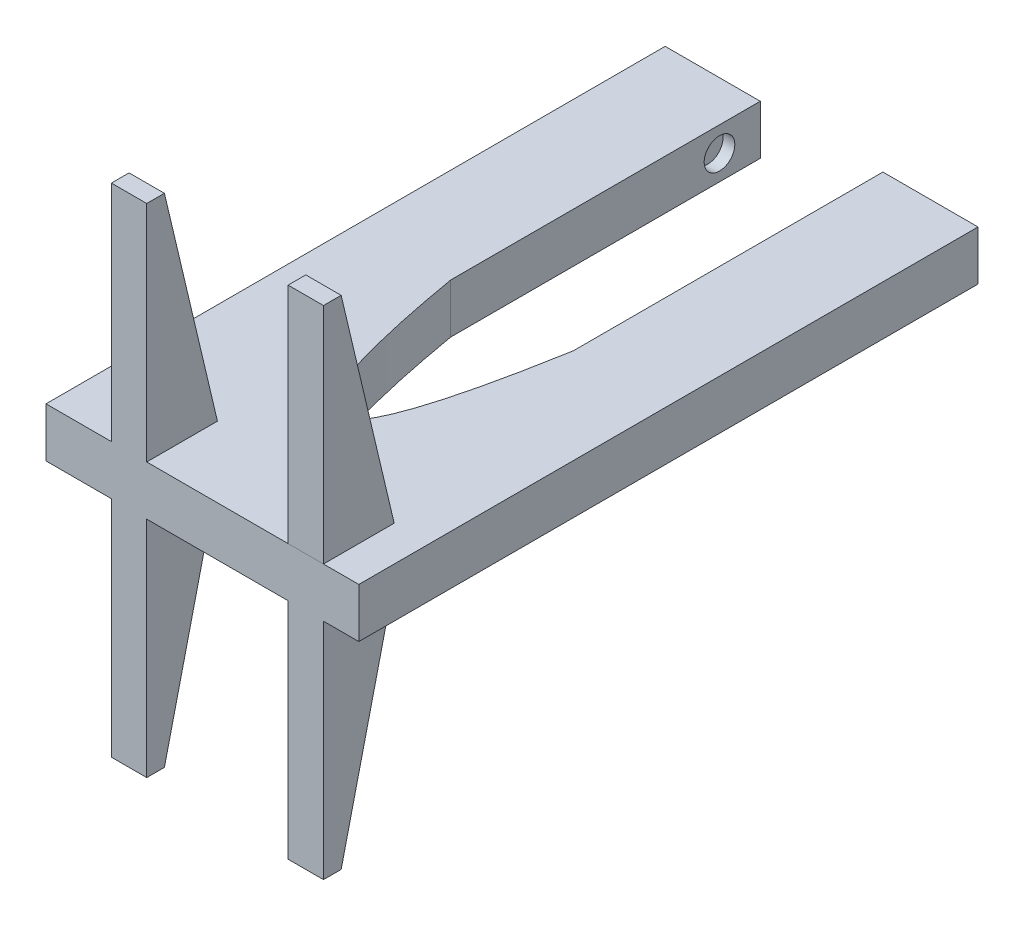
SolidWorks part; units mm, degrees
material "Ductile Iron"
ref_plane "Front Plane" through (0, 0, 0) normal (0, 0, 1) x (1, 0, 0)
ref_plane "Top Plane" through (0, 0, 0) normal (0, 1, 0) x (1, 0, 0)
ref_plane "Right Plane" through (0, 0, 0) normal (1, 0, 0) x (0, 0, -1)
sketch "Sketch1" plane through (0, 0, 0) normal (0, 1, 0) x (1, 0, 0)
  line L1 (300, 0) -> (300, -5255)
  line L2 (300, -5255) -> (-2355, -5255)
  line L3 (-2355, -5255) -> (-2355, -4455)
  line L6 (-2355, 0) -> (-2355, -4455)
  line L8 (-2355, 0) -> (-1548, 0)
  line L9 (300, 0) -> (-507, 0)
  line L10 (-1548, 0) -> (-1548, -2627.5)
  line L11 (-507, 0) -> (-507, -2627.5)
  spline S0 degree 2 poles (-1548, -2627.5) (-1027.5, -5612.8869) (-507, -2627.5) knots 0 0 0 1 1 1
  point P12 (0, 0)
  point P13 (0, 0)
  dimension "D5" = 807
  dimension "D1" = 5255
  dimension "D2" = 2655
  dimension "D3" = 800
  dimension "D6" = 807
extrude "Boss-Extrude1" add sketch "Sketch1" along normal blind 420
ref_plane "Plane1" through (0, 0, 0) normal (1, 0, 0) x (0, 0, -1)
ref_plane "Plane2" through (-1800, 0, 0) normal (1, 0, 0) x (0, 0, -1)
sketch "Sketch2" plane through (-1800, 0, 0) normal (1, 0, 0) x (0, 0, -1)
  line L0 (-5255, 420) -> (-5255, 2320)
  line L1 (-5105, 2320) -> (-4655, 420)
  line L2 (-5255, 420) -> (0, 420) construction
  line L3 (-4655, 420) -> (-5255, 420)
  line L4 (-5255, 2320) -> (-5105, 2320)
  line L5 (-5255, 420) -> (-5255, 0) construction
  dimension "D1" = 1900
  dimension "D2" = 150
  dimension "D3" = 600
extrude "Boss-Extrude2" add sketch "Sketch2" along normal blind 300
sketch "Sketch3" plane through (0, 0, 0) normal (1, 0, 0) x (0, 0, -1)
  line L0 (-5255, 420) -> (-5255, 2320)
  line L1 (-5255, 2320) -> (-5105, 2320)
  line L2 (-5105, 2320) -> (-4655, 420)
  line L3 (-5255, 420) -> (0, 420) construction
  line L4 (-4655, 420) -> (-5105, 2320) construction
  line L5 (-4655, 420) -> (-5255, 420)
  line L6 (-5255, 420) -> (-5255, 0) construction
extrude "Boss-Extrude3" add sketch "Sketch3" against normal blind 300 separate body
ref_plane "Plane3" through (0, 210, 0) normal (0, 1, 0) x (1, 0, 0)
mirror "Mirror13" about plane through (0, 210, 0) normal (0, 1, 0) of "Boss-Extrude3"
mirror "Mirror14" about plane through (0, 210, 0) normal (0, 1, 0) of "Boss-Extrude2"
sketch "Sketch4" plane through (300, 0, 0) normal (1, 0, 0) x (0, 0, -1)
  circle A0 centre (-346.012, 210) radius 130
extrude "Cut-Extrude2" cut sketch "Sketch4" against normal blind 1242 from offset 706 contours A0
